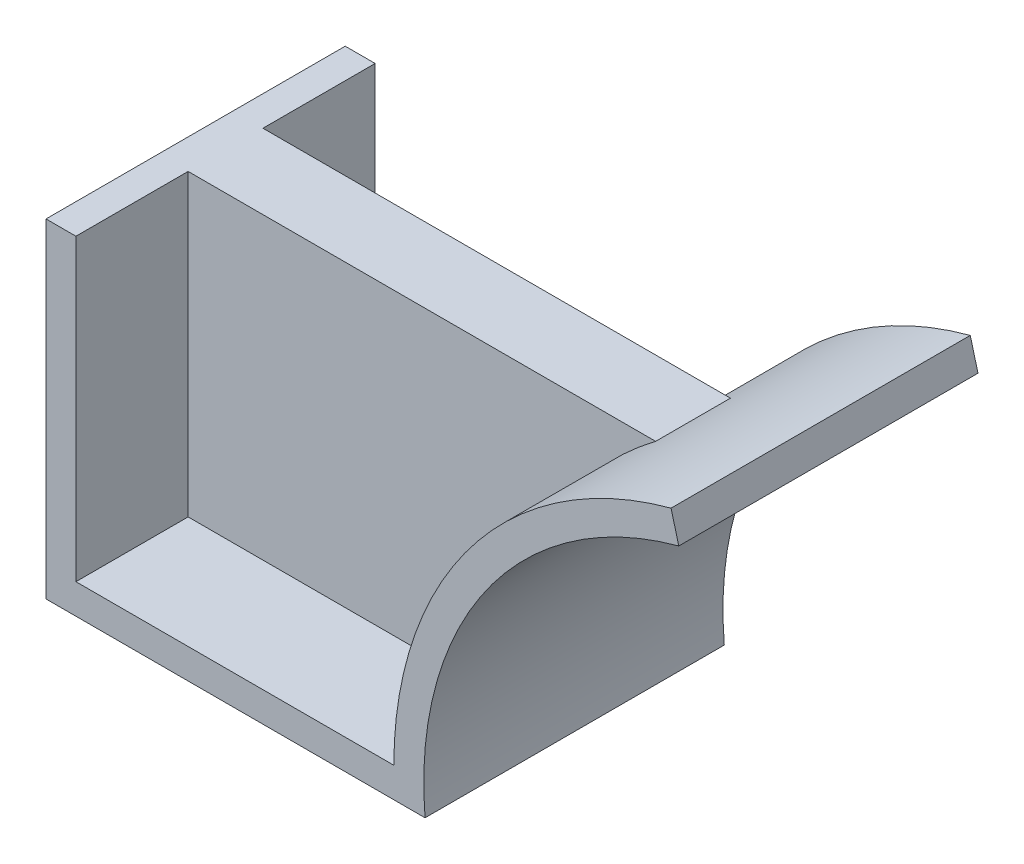
SolidWorks part; units mm, degrees
ref_plane "Front Plane" through (0, 0, 0) normal (0, 0, 1) x (1, 0, 0)
ref_plane "Top Plane" through (0, 0, 0) normal (0, 1, 0) x (1, 0, 0)
ref_plane "Right Plane" through (0, 0, 0) normal (1, 0, 0) x (0, 0, -1)
sketch "Sketch1" plane through (0, 0, 0) normal (0, 0, 1) x (1, 0, 0)
  line L0 (0, 80) -> (0, 0)
  line L1 (0, 0) -> (85, 0)
  line L2 (185, 0) -> (85, 0) construction
  line L3 (185, 0) -> (159.1181, 96.5926) construction
  arc A0 (85, 0) -> (159.1181, 96.5926) centre (185, 0) cw
  dimension "D3" = 100
  dimension "D1" = 80
  dimension "D2" = 85
  dimension "D4" = 75
extrude "Extrude-Thin1" add sketch "Sketch1" along normal blind 80 thin
sketch "Sketch2" plane through (0, 0, 0) normal (1, 0, 0) x (0, 0, -1)
  line L0 (-80, 80) -> (0, 80) construction
  line L1 (-50, 80) -> (-30, 80)
  line L2 (-50, 80) -> (-50, 0)
  line L3 (-50, 0) -> (-30, 0)
  line L4 (-30, 80) -> (-30, 0)
  line L5 (-80, 0) -> (0, 0) construction
  line L6 (0, 0) -> (-30, 0) construction
  line L7 (-50, 0) -> (-80, 0) construction
  dimension "D1" = 20
extrude "Boss-Extrude1" add sketch "Sketch2" along normal up to surface (125 mm away)
